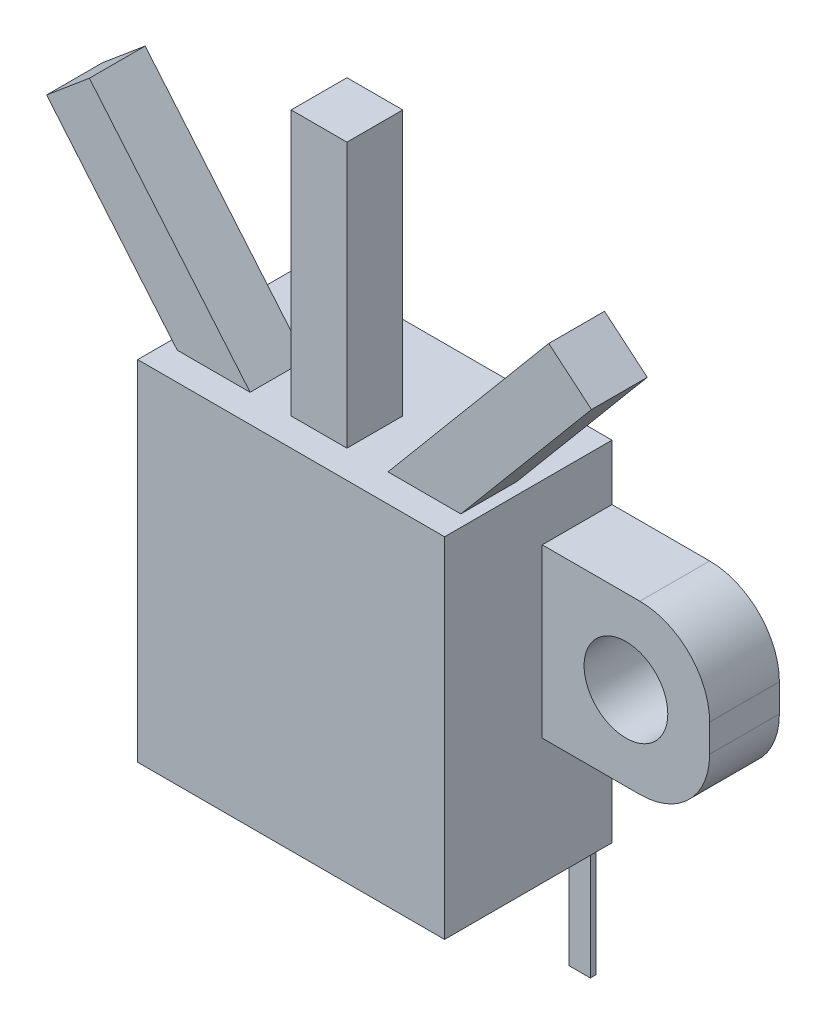
SolidWorks part; units mm, degrees
ref_plane "Front Plane" through (0, 0, 0) normal (0, 0, 1) x (1, 0, 0)
ref_plane "Top Plane" through (0, 0, 0) normal (0, 1, 0) x (1, 0, 0)
ref_plane "Right Plane" through (0, 0, 0) normal (1, 0, 0) x (0, 0, -1)
sketch "Skica1" plane through (0, 0, 0) normal (0, 0, 1) x (1, 0, 0)
  line L0 (0, 0) -> (0, 12.5)
  line L1 (0, 12.5) -> (11, 12.5)
  line L2 (11, 12.5) -> (11, 10.5)
  line L3 (11, 10.5) -> (17, 10.5)
  line L4 (17, 10.5) -> (17, 4.5)
  line L5 (17, 4.5) -> (11, 4.5)
  line L6 (11, 4.5) -> (11, 0)
  line L7 (11, 0) -> (0, 0)
  dimension "D1" = 12.5
  dimension "D2" = 11
  dimension "D3" = 6
  dimension "D4" = 17
  dimension "D5" = 2
extrude "Přidat vysunutím1" add sketch "Skica1" along normal blind 6
sketch "Skica2" plane through (0, 0, 6) normal (0, 0, 1) x (1, 0, 0)
  line L1 (17, 10.5) -> (11, 10.5)
  line L2 (17, 10.5) -> (17, 4.5)
  line L3 (17, 4.5) -> (11, 4.5)
  line L4 (11, 10.5) -> (11, 4.5)
extrude "Odebrat vysunutím1" cut sketch "Skica2" against normal blind 3.5
sketch "Skica3" plane through (0, 0, 2.5) normal (0, 0, 1) x (1, 0, 0)
  line L0 (17, 7.5) -> (11, 7.5) construction
  line L1 (17, 4.5) -> (17, 10.5) construction
  line L2 (11, 10.5) -> (11, 4.5) construction
  circle A0 centre (14, 7.5) radius 1.5
  dimension "D1" = 3
  dimension "D2" = 1.5
extrude "Odebrat vysunutím2" cut sketch "Skica3" against normal blind 3.5
sketch "Skica4" plane through (0, 0, 0) normal (0, 0, -1) x (-1, 0, 0)
  line L0 (0, 0) -> (-11, 0) construction
  line L1 (-10.423, 0) -> (-9.6578, 0)
  line L2 (-10.423, 0) -> (-10.423, -4.3844)
  line L3 (-10.423, -4.3844) -> (-9.6578, -4.3844)
  line L4 (-9.6578, 0) -> (-9.6578, -4.3844)
  line L6 (-5.8064, 0) -> (-5.2197, 0)
  line L7 (-5.8064, 0) -> (-5.8064, -4.3844)
  line L8 (-5.8064, -4.3844) -> (-5.2197, -4.3844)
  line L9 (-5.2197, 0) -> (-5.2197, -4.3844)
  line L10 (-1.1897, 0) -> (-0.6796, 0)
  line L11 (-1.1897, 0) -> (-1.1897, -4.3844)
  line L12 (-1.1897, -4.3844) -> (-0.6796, -4.3844)
  line L13 (-0.6796, 0) -> (-0.6796, -4.3844)
extrude "Přidat vysunutím2" add sketch "Skica4" against normal blind 0.2
ref_plane "Rovina1" through (0, 0, 5) normal (0, 0, 1) x (1, 0, 0)
sketch "Skica5" plane through (0, 0, 5) normal (0, 0, 1) x (1, 0, 0)
  line L0 (11, 12.5) -> (0, 12.5) construction
  line L1 (4.5, 12.5) -> (6.5, 12.5)
  line L2 (4.5, 12.5) -> (4.5, 22)
  line L3 (4.5, 22) -> (6.5, 22)
  line L4 (6.5, 12.5) -> (6.5, 22)
  line L5 (11, 0) -> (11, 12.5) construction
  line L6 (5.5, 22) -> (5.5, 8) construction
  line L7 (7.6265, 12.09) -> (13.733, 19.3674)
  line L8 (7.6265, 12.09) -> (9.1586, 10.8044)
  line L9 (9.1586, 10.8044) -> (15.2651, 18.0818)
  line L10 (13.733, 19.3674) -> (15.2651, 18.0818)
  line L11 (5.5, 8) -> (6.5, 12.5) construction
  line L12 (5.5, 8) -> (9.1586, 10.8044) construction
  line L13 (1.8414, 10.8044) -> (-4.2651, 18.0818)
  line L14 (1.8414, 10.8044) -> (3.3735, 12.09)
  line L15 (3.3735, 12.09) -> (-2.733, 19.3674)
  line L16 (-4.2651, 18.0818) -> (-2.733, 19.3674)
  line L17 (5.5, 8) -> (6.5, 12.5) construction
  line L18 (5.5, 8) -> (3.3735, 12.09) construction
  point P11 (5.5, 8)
  dimension "D1" = 9.5
  dimension "D2" = 2
  dimension "D3" = 4.5
  dimension "D4" = 14
  dimension "D6" = 40
  dimension "D8" = 40
  dimension "D5" = 2
  dimension "D7" = 2
extrude "Přidat vysunutím3" add sketch "Skica5" against normal blind 2
sketch "Skica6" plane through (0, 0, 0) normal (0, 0, -1) x (-1, 0, 0)
  line L0 (-5.5, 12.5) -> (-5.5, 7.5) construction
  line L1 (-11, 12.5) -> (0, 12.5) construction
  circle A0 centre (-5.5, 7.5) radius 1
  dimension "D1" = 2
  dimension "D2" = 4
extrude "Přidat vysunutím4" add sketch "Skica6" along normal blind 1.8
fillet "Zaoblit1" radius 2.5 2 edges at (17, 4.5, 1.25) (17, 10.5, 1.25)
sketch "Skica7" plane through (0, 12.5, 0) normal (0, 1, 0) x (1, 0, 0)
  line L0 (11, -6) -> (16, 15) construction
  point P4 (0, 0)
  point P5 (0, 0)
  dimension "D1" = 21
  dimension "D2" = 5
